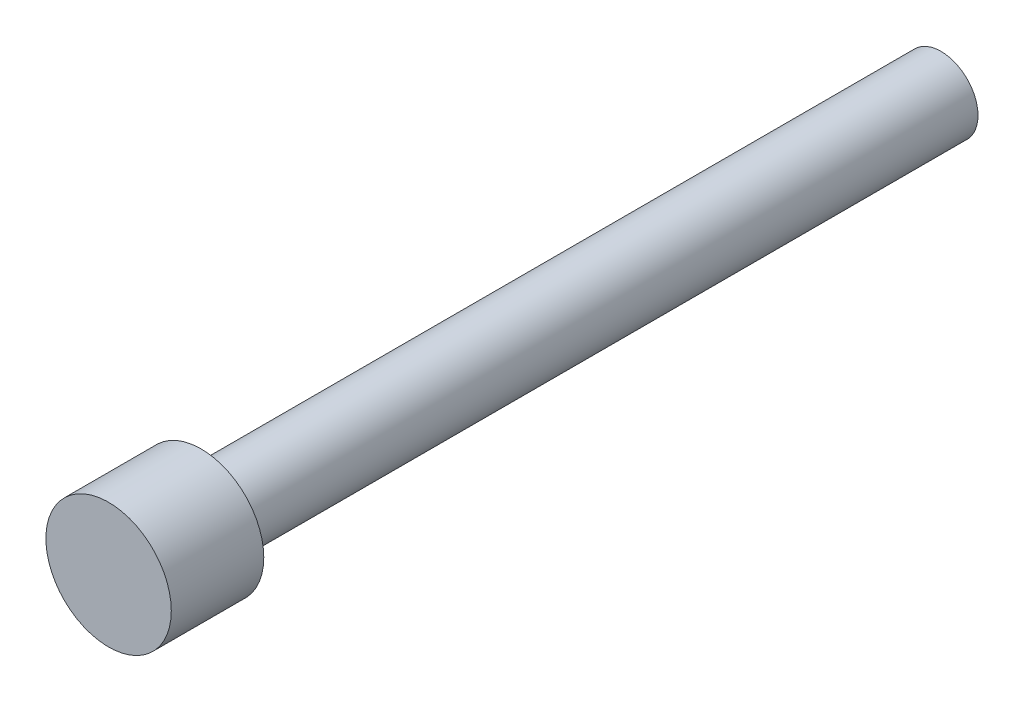
SolidWorks part; units mm, degrees
ref_plane "Front Plane" through (0, 0, 0) normal (0, 0, 1) x (1, 0, 0)
ref_plane "Top Plane" through (0, 0, 0) normal (0, 1, 0) x (1, 0, 0)
ref_plane "Right Plane" through (0, 0, 0) normal (1, 0, 0) x (0, 0, -1)
sketch "Sketch1" plane through (0, 0, 0) normal (0, 0, 1) x (1, 0, 0)
  circle A0 centre (0, 0) radius 2
extrude "Boss-Extrude1" add sketch "Sketch1" along normal blind 40
sketch "Sketch2" plane through (0, 0, 40) normal (0, 0, 1) x (1, 0, 0)
  circle A0 centre (0, 0) radius 3.39
extrude "Boss-Extrude2" add sketch "Sketch2" along normal blind 5
